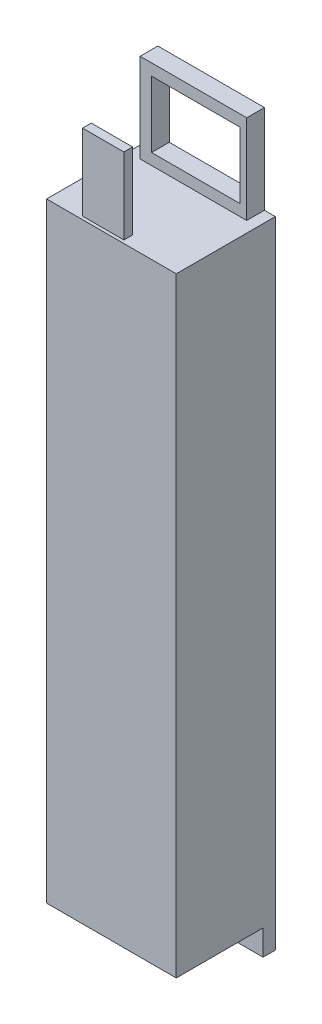
SolidWorks part; units mm, degrees
ref_plane "前视基准面" through (0, 0, 0) normal (0, 0, 1) x (1, 0, 0)
ref_plane "上视基准面" through (0, 0, 0) normal (0, 1, 0) x (1, 0, 0)
ref_plane "右视基准面" through (0, 0, 0) normal (1, 0, 0) x (0, 0, -1)
sketch "草图1" plane through (0, 0, 0) normal (0, 1, 0) x (1, 0, 0)
  line L1 (0, 0) -> (51, 0)
  line L2 (0, 0) -> (0, 39)
  line L3 (0, 39) -> (51, 39)
  line L4 (51, 0) -> (51, 39)
  dimension "D1" = 51
  dimension "D2" = 39
extrude "凸台-拉伸1" add sketch "草图1" along normal blind 240
sketch "草图2" plane through (0, 240, 0) normal (0, 1, 0) x (1, 0, 0)
  line L0 (51, 39) -> (0, 39) construction
  line L1 (4.7441, 39) -> (46.7052, 39)
  line L2 (4.7441, 39) -> (4.7441, 32.0289)
  line L3 (4.7441, 32.0289) -> (46.7052, 32.0289)
  line L4 (46.7052, 39) -> (46.7052, 32.0289)
extrude "凸台-拉伸2" add sketch "草图2" along normal blind 35
sketch "草图3" plane through (0, 240, 0) normal (0, 1, 0) x (1, 0, 0)
  line L1 (12.9317, 4.6369) -> (29.1765, 4.6369)
  line L2 (12.9317, 4.6369) -> (12.9317, 1.217)
  line L3 (12.9317, 1.217) -> (29.1765, 1.217)
  line L4 (29.1765, 4.6369) -> (29.1765, 1.217)
extrude "凸台-拉伸3" add sketch "草图3" along normal blind 30
sketch "草图4" plane through (0, 0, 0) normal (0, -1, 0) x (1, 0, 0)
  line L0 (51, 0) -> (51, -39) construction
  line L1 (0, -39) -> (51, -39)
  line L2 (0, -39) -> (0, -34.1582)
  line L3 (0, -34.1582) -> (51, -34.1582)
  line L4 (51, -39) -> (51, -34.1582)
extrude "凸台-拉伸4" add sketch "草图4" along normal blind 10
sketch "草图5" plane through (0, 0, 0) normal (0, -1, 0) x (1, 0, 0)
  line L1 (3.6149, -3.2617) -> (48.3213, -3.2617)
  line L2 (3.6149, -3.2617) -> (3.6149, -32.2858)
  line L3 (3.6149, -32.2858) -> (48.3213, -32.2858)
  line L4 (48.3213, -3.2617) -> (48.3213, -32.2858)
extrude "切除-拉伸1" cut sketch "草图5" against normal blind 10
sketch "草图6" plane through (0, 0, -32.0289) normal (0, 0, 1) x (1, 0, 0)
  line L1 (9.2507, 270.4773) -> (43.9662, 270.4773)
  line L2 (9.2507, 270.4773) -> (9.2507, 244.4407)
  line L3 (9.2507, 244.4407) -> (43.9662, 244.4407)
  line L4 (43.9662, 270.4773) -> (43.9662, 244.4407)
extrude "切除-拉伸2" cut sketch "草图6" against normal blind 10
